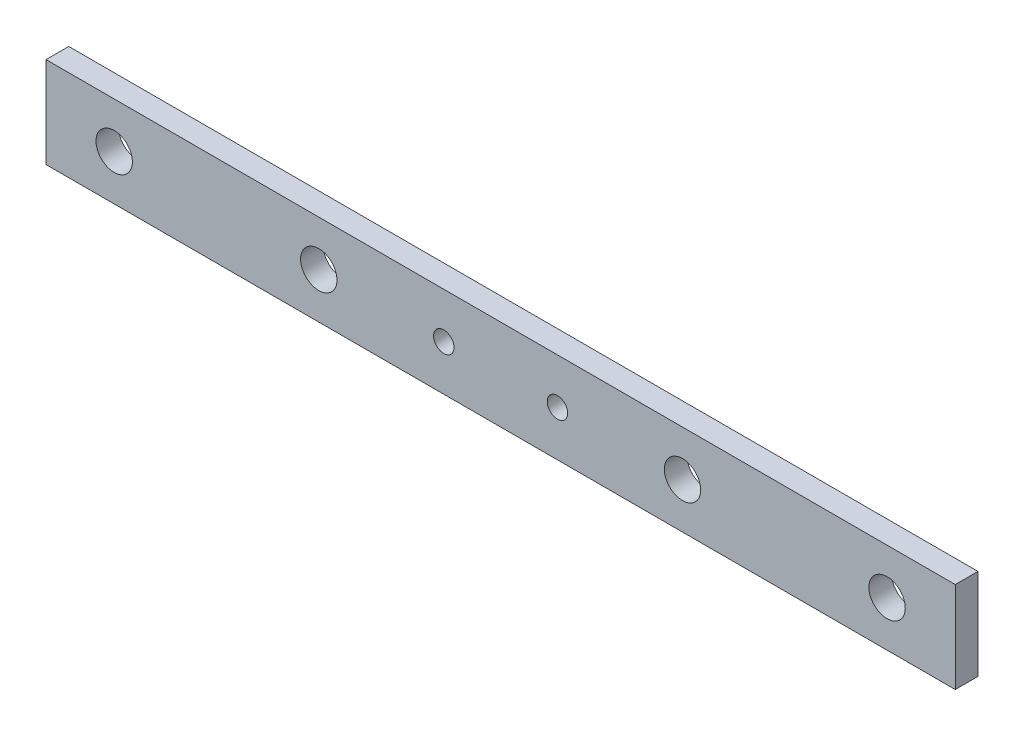
SolidWorks part; units mm, degrees
ref_plane "Plan de face" through (0, 0, 0) normal (0, 0, 1) x (1, 0, 0)
ref_plane "Plan de dessus" through (0, 0, 0) normal (0, 1, 0) x (1, 0, 0)
ref_plane "Plan de droite" through (0, 0, 0) normal (1, 0, 0) x (0, 0, -1)
sketch "Esquisse1" plane through (0, 0, 0) normal (0, 0, 1) x (1, 0, 0)
  line L0 (-100, 0) -> (100, 0) construction
  line L5 (-100, -10) -> (100, -10)
  line L6 (-100, -10) -> (-100, 10)
  line L7 (-100, 10) -> (100, 10)
  line L8 (100, -10) -> (100, 10)
  line L9 (-100, -10) -> (100, 10) construction
  line L10 (-100, 10) -> (100, -10) construction
  line L11 (0, -1000) -> (0, 49000) construction
  line L12 (-100, -10) -> (-100, 10)
  line L13 (100, -10) -> (100, 10)
  circle A6 centre (-85, 0) radius 4
  circle A7 centre (-40, 0) radius 4
  circle A8 centre (40, 0) radius 4
  circle A9 centre (85, 0) radius 4
  circle A10 centre (-12.5, 0) radius 2.25
  circle A11 centre (12.5, 0) radius 2.25
  point P0 (0, 0)
  dimension "D1" = 200
  dimension "D3" = 4.5
  dimension "D4" = 8
  dimension "D2" = 20
  dimension "D5" = 15
  dimension "D6" = 40
  dimension "D7" = 25
extrude "Boss.-Extru.1" add sketch "Esquisse1" along normal blind 5 contours L5 L8 L7 L6 A9 A6 A7 A8 A10 A11
